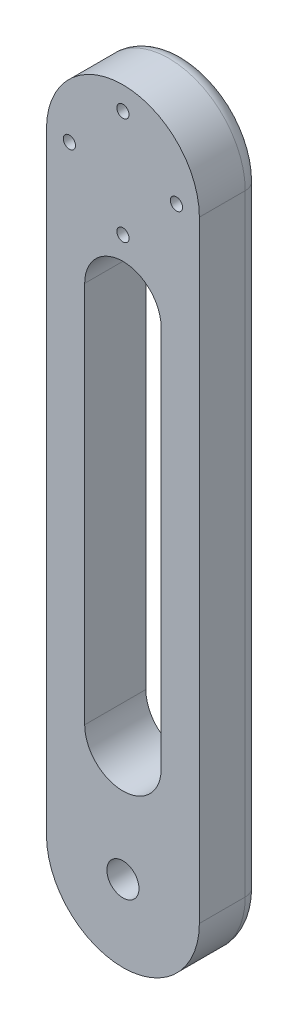
SolidWorks part; units mm, degrees
material "ABS"
ref_plane "Front Plane" through (0, 0, 0) normal (0, 0, 1) x (1, 0, 0)
ref_plane "Top Plane" through (0, 0, 0) normal (0, 1, 0) x (1, 0, 0)
ref_plane "Right Plane" through (0, 0, 0) normal (1, 0, 0) x (0, 0, -1)
sketch "Sketch1" plane through (0, 0, 0) normal (0, 0, 1) x (1, 0, 0)
  line L0 (-10, 0) -> (-10, -80)
  line L1 (-10, -80) -> (10, -80)
  line L2 (10, -80) -> (10, 0)
  circle A0 centre (0, 0) radius 10
  circle A1 centre (0, 7) radius 0.8
  circle A2 centre (7, 0) radius 0.8
  circle A3 centre (0, -7) radius 0.8
  circle A4 centre (-7, 0) radius 0.8
  circle A5 centre (0, -80) radius 10
  circle A6 centre (0, -80) radius 2.1
  point P14 (0, 0)
  dimension "D1" = 20
  dimension "D2" = 1.6
  dimension "D3" = 7
  dimension "D4" = 0
  dimension "D7" = 4.2
  dimension "D6" = 80
  dimension "D5" = 4
extrude "Boss-Extrude1" add sketch "Sketch1" along normal blind 8 contours A5 L2 A0 L0 | A0 A4 A3 A2 A1 | A6 L1 A5 | A6 L1 A5
fillet "Fillet1" radius 2 4 edges at (0, -90, 0) (0, 10, 0) (-10, -40, 0) (10, -40, 0)
sketch "Sketch3" plane through (0, 0, 0) normal (0, 0, -1) x (-1, 0, 0)
  line L0 (0, -65) -> (0, -15) construction
  line L1 (-5, -65) -> (-5, -15)
  line L2 (5, -65) -> (5, -15)
  arc A0 (-5, -65) -> (5, -65) centre (0, -65) ccw
  arc A1 (5, -15) -> (-5, -15) centre (0, -15) ccw
  point P2 (0, -40)
  dimension "D1" = 5
  dimension "D2" = 50
  dimension "D3" = 40
extrude "Cut-Extrude1" cut sketch "Sketch3" against normal blind 60
